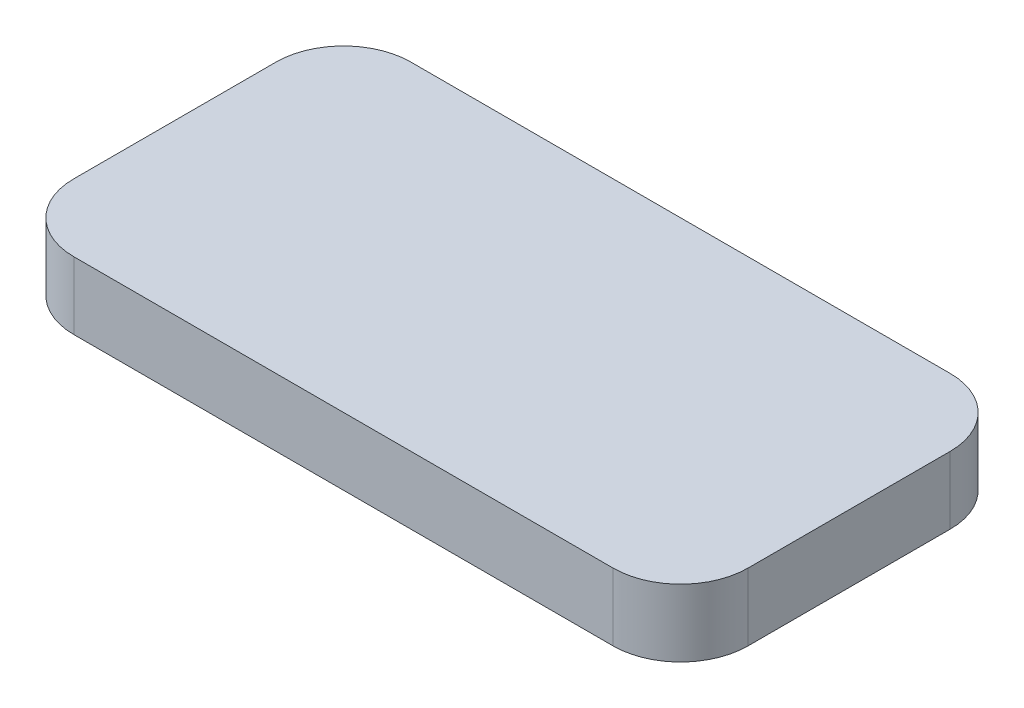
SolidWorks part; units mm, degrees
ref_plane "Front Plane" through (0, 0, 0) normal (0, 0, 1) x (1, 0, 0)
ref_plane "Top Plane" through (0, 0, 0) normal (0, 1, 0) x (1, 0, 0)
ref_plane "Right Plane" through (0, 0, 0) normal (1, 0, 0) x (0, 0, -1)
sketch "Sketch1" plane through (0, 0, 0) normal (0, 1, 0) x (1, 0, 0)
  line L1 (-50, -25) -> (50, -25)
  line L2 (-50, -25) -> (-50, 25)
  line L3 (-50, 25) -> (50, 25)
  line L4 (50, -25) -> (50, 25)
  line L5 (-50, -25) -> (50, 25) construction
  line L6 (-50, 25) -> (50, -25) construction
  point P0 (0, 0)
  dimension "D1" = 100
  dimension "D2" = 50
extrude "Boss-Extrude1" add sketch "Sketch1" along normal blind 10
fillet "Fillet1" radius 10 4 edges at (-50, 5, -25) (50, 5, -25) (50, 5, 25) (-50, 5, 25)
